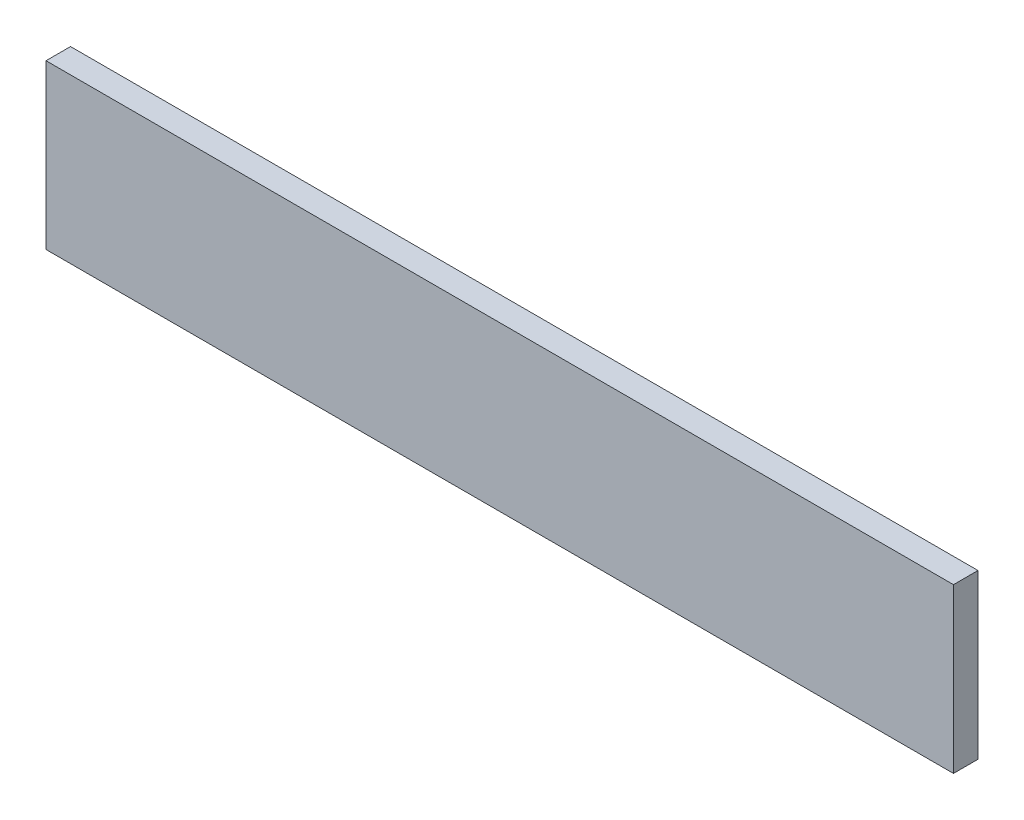
SolidWorks part; units mm, degrees
ref_plane "Front Plane" through (0, 0, 0) normal (0, 0, 1) x (1, 0, 0)
ref_plane "Top Plane" through (0, 0, 0) normal (0, 1, 0) x (1, 0, 0)
ref_plane "Right Plane" through (0, 0, 0) normal (1, 0, 0) x (0, 0, -1)
sketch "Sketch1" plane through (0, 0, 0) normal (0, 0, 1) x (1, 0, 0)
  line L1 (0, 0) -> (704.85, 0)
  line L2 (0, 0) -> (0, 127)
  line L3 (0, 127) -> (704.85, 127)
  line L4 (704.85, 0) -> (704.85, 127)
  dimension "D1" = 127
  dimension "D2" = 704.85
extrude "Boss-Extrude1" add sketch "Sketch1" along normal blind 19.05
